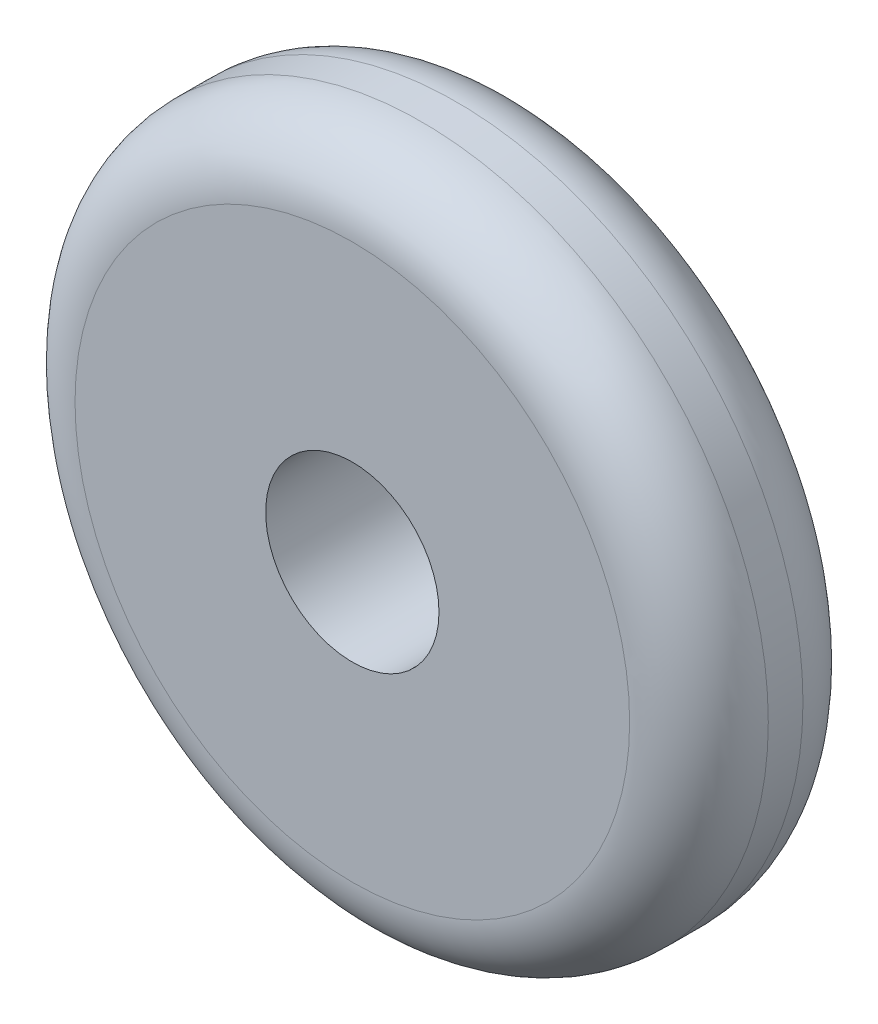
SolidWorks part; units mm, degrees
ref_plane "Front Plane" through (0, 0, 0) normal (0, 0, 1) x (1, 0, 0)
ref_plane "Top Plane" through (0, 0, 0) normal (0, 1, 0) x (1, 0, 0)
ref_plane "Right Plane" through (0, 0, 0) normal (1, 0, 0) x (0, 0, -1)
sketch "Sketch1" plane through (0, 0, 0) normal (0, 0, 1) x (1, 0, 0)
  circle A0 centre (0, 0) radius 25.4
  circle A1 centre (0, 0) radius 6.35
  dimension "D1" = 50.8
  dimension "D2" = 12.7
extrude "Boss-Extrude1" add sketch "Sketch1" along normal blind 12.7
fillet "Fillet1" radius 5.08 2 edges at (25.4, 0, 0) (25.4, 0, 12.7)
